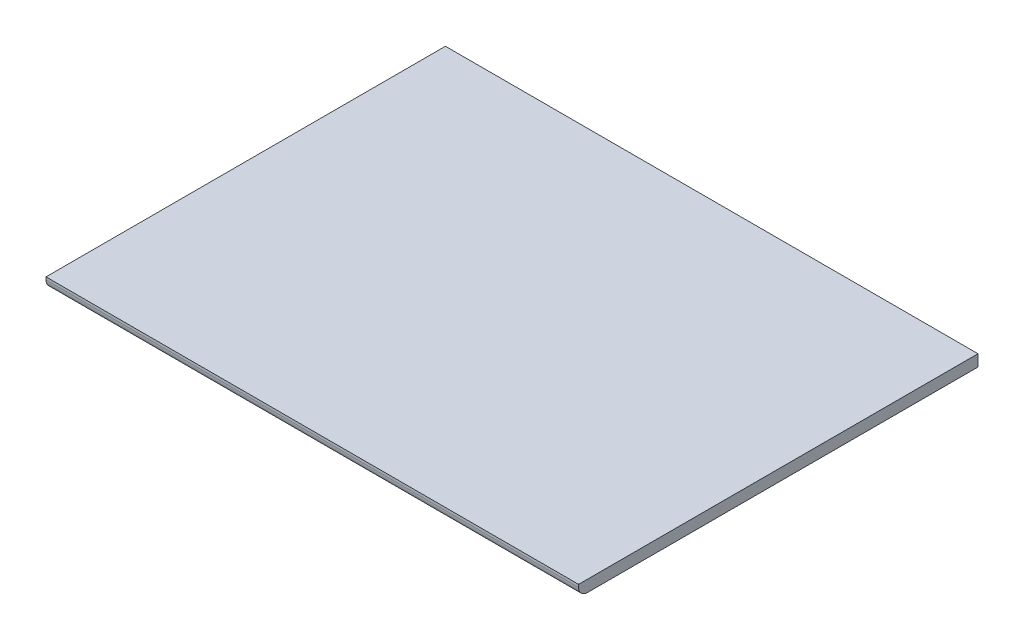
SolidWorks part; units mm, degrees
ref_plane "前视基准面" through (0, 0, 0) normal (0, 0, 1) x (1, 0, 0)
ref_plane "上视基准面" through (0, 0, 0) normal (0, 1, 0) x (1, 0, 0)
ref_plane "右视基准面" through (0, 0, 0) normal (1, 0, 0) x (0, 0, -1)
sketch "草图1" plane through (0, 0, 0) normal (0, 1, 0) x (1, 0, 0)
  line L1 (-7.375, 4) -> (7.375, 4)
  line L2 (-7.375, 4) -> (-7.375, -4)
  line L3 (-7.375, -4) -> (7.375, -4)
  line L4 (7.375, 4) -> (7.375, -4)
  line L5 (-7.375, 4) -> (7.375, -4) construction
  line L6 (-7.375, -4) -> (7.375, 4) construction
  point P0 (0, 0)
  dimension "D1" = 14.75
  dimension "D2" = 8
extrude "凸台-拉伸1" add sketch "草图1" along normal blind 1.2
sketch "草图2" plane through (0, 1.2, 0) normal (0, 1, 0) x (1, 0, 0)
  line L0 (7.375, -4) -> (7.375, 4) construction
  line L1 (-7.375, 4) -> (7.375, 4)
  line L2 (-7.375, 4) -> (-7.375, 0.1)
  line L3 (-7.375, 0.1) -> (7.375, 0.1)
  line L4 (7.375, 4) -> (7.375, 0.1)
  dimension "D1" = 3.9
extrude "凸台-拉伸2" add sketch "草图2" along normal blind 1.55
sketch "草图3" plane through (0, 2.75, 0) normal (0, 1, 0) x (1, 0, 0)
  line L0 (0, 0) -> (0, -6.5443) construction
  line L1 (-30, 4) -> (30, 4)
  line L2 (-30, 4) -> (-30, -41)
  line L3 (-30, -41) -> (30, -41)
  line L4 (30, 4) -> (30, -41)
  line L5 (7.375, 4) -> (-7.375, 4) construction
  dimension "D1" = 60
  dimension "D2" = 45
extrude "凸台-拉伸3" add sketch "草图3" along normal blind 1.3
fillet "圆角1" radius 3 1 edges at (0, 0, -4)
fillet "圆角2" radius 1 1 edges at (0, 1.2, 4)
fillet "圆角3" radius 1 1 edges at (0, 2.75, 41)
